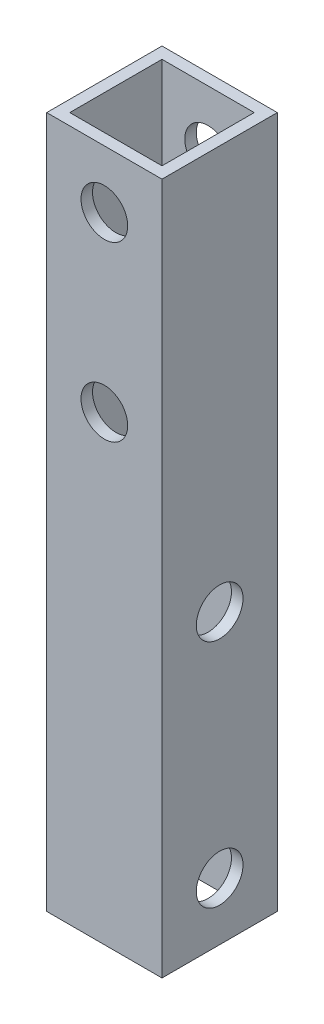
SolidWorks part; units mm, degrees
material "1345 Alloy"
ref_plane "Front Plane" through (0, 0, 0) normal (0, 0, 1) x (1, 0, 0)
ref_plane "Top Plane" through (0, 0, 0) normal (0, 1, 0) x (1, 0, 0)
ref_plane "Right Plane" through (0, 0, 0) normal (1, 0, 0) x (0, 0, -1)
sketch "Sketch1" plane through (0, 0, 0) normal (0, 1, 0) x (1, 0, 0)
  line L1 (-5, 5) -> (5, 5)
  line L2 (-5, 5) -> (-5, -5)
  line L3 (-5, -5) -> (5, -5)
  line L4 (5, 5) -> (5, -5)
  line L5 (-5, 5) -> (5, -5) construction
  line L6 (-5, -5) -> (5, 5) construction
  line L7 (-4, 4) -> (4, 4)
  line L8 (-4, 4) -> (-4, -4)
  line L9 (-4, -4) -> (4, -4)
  line L10 (4, 4) -> (4, -4)
  line L11 (-4, 4) -> (4, -4) construction
  line L12 (-4, -4) -> (4, 4) construction
  point P0 (0, 0)
  point P6 (0, 0)
  dimension "D1" = 10
  dimension "D2" = 10
  dimension "D3" = 8
  dimension "D4" = 8
extrude "Boss-Extrude1" add sketch "Sketch1" along normal blind 60
sketch "Sketch2" plane through (5, 0, 0) normal (1, 0, 0) x (0, 0, -1)
  line L0 (0, -3.5928) -> (0, 103.2334) construction
  line L1 (-5, 0) -> (5, 0) construction
  circle A0 centre (0, 5) radius 2.025
  circle A1 centre (0, 25) radius 2.025
  dimension "D1" = 4.05
  dimension "D2" = 4.05
  dimension "D3" = 20
  dimension "D4" = 5
extrude "Cut-Extrude1" cut sketch "Sketch2" against normal through all
sketch "Sketch4" plane through (0, 0, 5) normal (0, 0, 1) x (1, 0, 0)
  line L0 (0, 61.7244) -> (0, -2.2635) construction
  line L1 (-5, 60) -> (5, 60) construction
  circle A0 centre (0, 55) radius 2.025
  circle A1 centre (0, 40) radius 2.025
  point P11 (0.3774, 45.9835)
  dimension "D1" = 4.05
  dimension "D2" = 4.05
  dimension "D3" = 5
  dimension "D4" = 15
extrude "Cut-Extrude2" cut sketch "Sketch4" against normal through all
